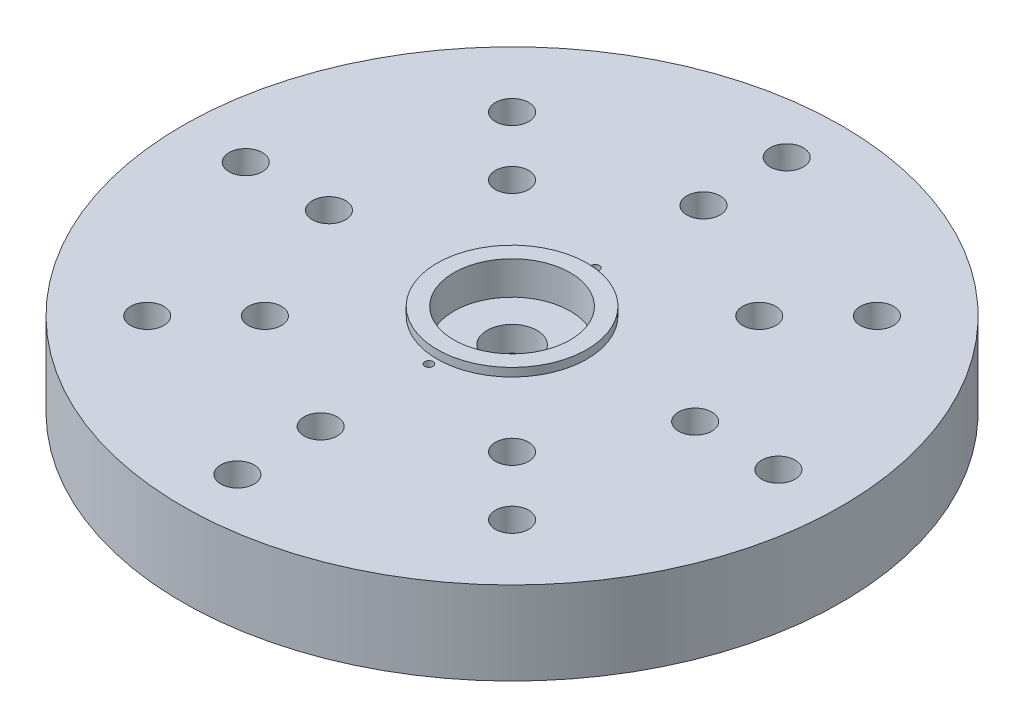
SolidWorks part; units mm, degrees
material "PVC rigide"
ref_plane "Plan de face" through (0, 0, 0) normal (0, 0, 1) x (1, 0, 0)
ref_plane "Plan de dessus" through (0, 0, 0) normal (0, 1, 0) x (1, 0, 0)
ref_plane "Plan de droite" through (0, 0, 0) normal (1, 0, 0) x (0, 0, -1)
sketch "Esquisse1" plane through (0, 0, 0) normal (0, 0, 1) x (1, 0, 0)
  line L0 (0, 0) -> (0, 8.5) construction
  line L1 (4, 0) -> (4, 5)
  line L2 (4, 5) -> (1.5, 5)
  line L3 (1.5, 5) -> (1.5, 6.5)
  line L4 (1.5, 6.5) -> (3.5, 6.5)
  line L5 (3.5, 6.5) -> (3.5, 8.5)
  line L6 (3.5, 8.5) -> (4.5, 8.5)
  line L7 (4.5, 8.5) -> (4.5, 8)
  line L8 (4.5, 8) -> (19.8, 8)
  line L9 (19.8, 8) -> (19.8, 3)
  line L10 (19.8, 3) -> (6, 3)
  line L11 (6, 3) -> (6, 0)
  line L12 (6, 0) -> (4, 0)
  dimension "D1" = 7
  dimension "D2" = 9
  dimension "D3" = 3
  dimension "D4" = 8
  dimension "D5" = 12
  dimension "D6" = 39.6
  dimension "D7" = 0.5
  dimension "D8" = 5
  dimension "D9" = 3
  dimension "D10" = 5
  dimension "D11" = 2
revolve "Révolution1" add sketch "Esquisse1" angle 360 about L0
sketch "Esquisse2" plane through (0, 8, 0) normal (0, 1, 0) x (1, 0, 0)
  line L0 (0, 16.5) -> (0, 0) construction
  line L1 (0, 0) -> (10.9602, 10.9602) construction
  line L2 (0, 0) -> (16, 0) construction
  line L3 (0, 0) -> (10.6066, -10.6066) construction
  circle A0 centre (0, 16.5) radius 1
  circle A1 centre (0, 0) radius 1.5 construction
  circle A2 centre (0, 11.5) radius 1
  circle A3 centre (0, 5) radius 0.25
  circle A4 centre (0, 0) radius 4.5 construction
  circle A5 centre (7.4246, 7.4246) radius 1
  circle A6 centre (10.9602, 10.9602) radius 1
  circle A7 centre (11, 0) radius 1
  circle A8 centre (16, 0) radius 1
  circle A9 centre (10.6066, -10.6066) radius 1
  circle A10 centre (7.0711, -7.0711) radius 1
  circle A11 centre (0, 0) radius 3.5 construction
  circle A12 centre (0, 0) radius 3.5 construction
  dimension "D1" = 2
  dimension "D2" = 16.5
  dimension "D3" = 11.5
  dimension "D4" = 5
  dimension "D5" = 0.5
  dimension "D6" = 10.5
  dimension "D10" = 11
  dimension "D11" = 16
  dimension "D12" = 10
  dimension "D13" = 15
  dimension "D7" = 15.5
  dimension "D8" = 45
  dimension "D9" = 45
extrude "Enlèv. mat.-Extru.1" cut sketch "Esquisse2" against normal blind 10
pattern_circular "Répétition circulaire1" count 2 over 360 about axis through (0, 0, 0) along (0, 1, 0) of "Enlèv. mat.-Extru.1"
